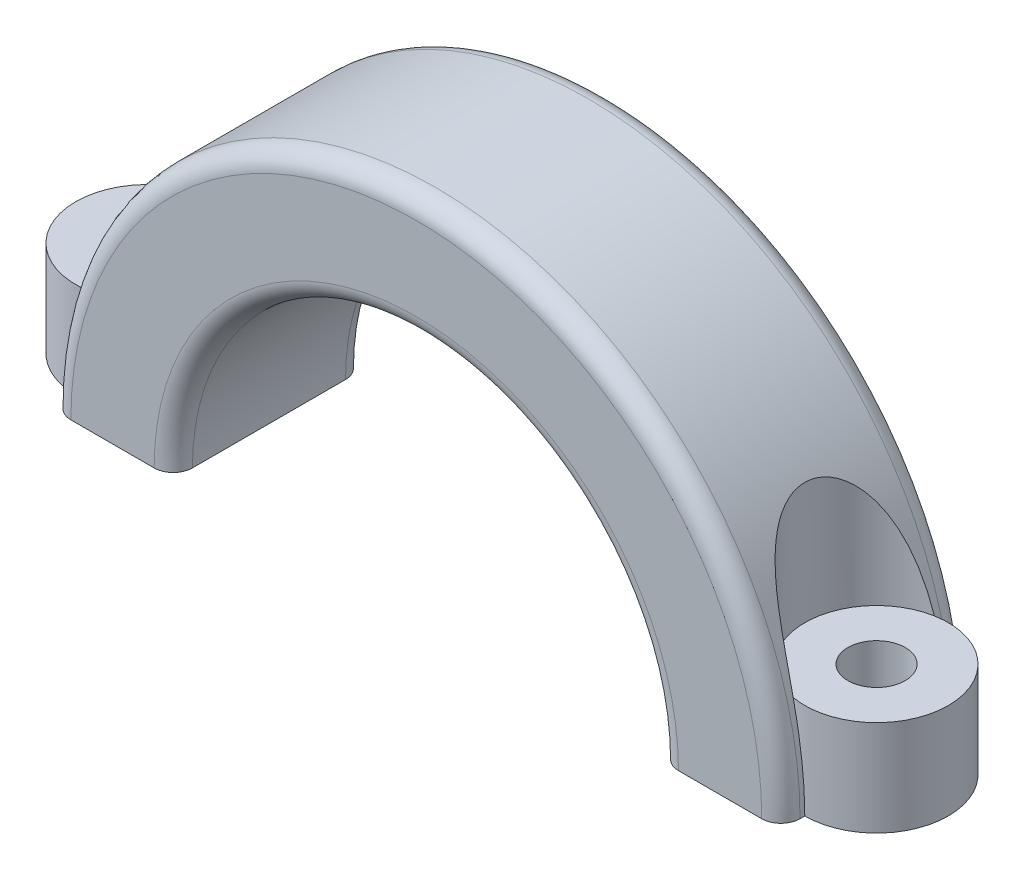
SolidWorks part; units mm, degrees
ref_plane "Front Plane" through (0, 0, 0) normal (0, 0, 1) x (1, 0, 0)
ref_plane "Top Plane" through (0, 0, 0) normal (0, 1, 0) x (1, 0, 0)
ref_plane "Right Plane" through (0, 0, 0) normal (1, 0, 0) x (0, 0, -1)
sketch "Sketch1" plane through (0, 0, 0) normal (0, 0, 1) x (1, 0, 0)
  line L0 (-38.1, 0) -> (-25.4, 0)
  line L1 (25.4, 0) -> (38.1, 0)
  arc A0 (25.4, 0) -> (-25.4, 0) centre (0, 0) ccw
  arc A1 (-38.1, 0) -> (38.1, 0) centre (0, 0) cw
  dimension "D1" = 25.4
  dimension "D2" = 38.1
extrude "Boss-Extrude1" add sketch "Sketch1" along normal mid plane 20
sketch "Sketch2" plane through (0, 0, 0) normal (0, -1, 0) x (1, 0, 0)
  line L0 (38.1, 10) -> (38.1, -10) construction
  circle A0 centre (38.1, 0) radius 7.5
  dimension "D1" = 15
extrude "Boss-Extrude4" add sketch "Sketch2" against normal blind 10
sketch "Sketch3" plane through (0, 10, 0) normal (0, 1, 0) x (1, 0, 0)
  circle A0 centre (38.1, 0) radius 7.5
  dimension "D1" = 15
extrude "Cut-Extrude1" cut sketch "Sketch3" along normal blind 60
sketch "Sketch4" plane through (0, 0, 0) normal (0, -1, 0) x (1, 0, 0)
  circle A0 centre (38.1, 0) radius 3
  dimension "D1" = 6
extrude "Cut-Extrude2" cut sketch "Sketch4" against normal blind 60
mirror "Mirror1" about plane through (0, 0, 0) normal (1, 0, 0) of "Cut-Extrude2", "Cut-Extrude1", "Boss-Extrude4"
fillet "Fillet1" radius 2 4 edges at (0, 25.4, -10) (0, 38.1, -10) (0, 38.1, 10) (0, 25.4, 10)
